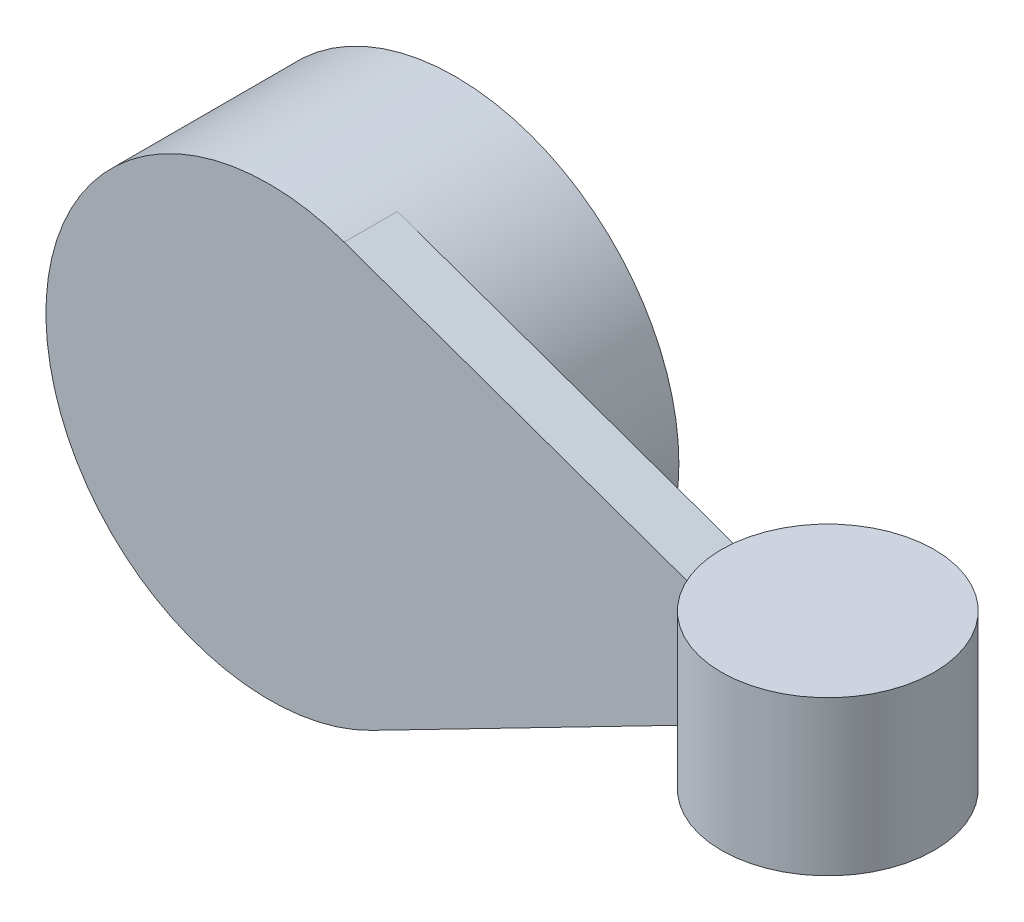
SolidWorks part; units mm, degrees
ref_plane "前视基准面" through (0, 0, 0) normal (0, 0, 1) x (1, 0, 0)
ref_plane "上视基准面" through (0, 0, 0) normal (0, 1, 0) x (1, 0, 0)
ref_plane "右视基准面" through (0, 0, 0) normal (1, 0, 0) x (0, 0, -1)
other "Configuration Table"
sketch "草图1" plane through (0, 0, 0) normal (0, 0, 1) x (1, 0, 0)
  circle A0 centre (0, 0) radius 42
  dimension "D1" = 84
extrude "凸台-拉伸1" add sketch "草图1" along normal blind 30
sketch "草图2" plane through (0, 0, 30) normal (0, 0, 1) x (1, 0, 0)
  line L0 (0, 0) -> (150.9371, 0) construction
  line L1 (100, 22.7173) -> (100, -21.6499) construction
  line L2 (100, 20) -> (100, 15)
  line L3 (80, 20) -> (100, 20)
  line L4 (80, 20) -> (80, -9)
  line L8 (80, -9) -> (88, -9)
  arc A1 (100, 15) -> (88, -9) centre (100, 0) ccw
  dimension "D2" = 30
  dimension "D1" = 100
  dimension "D3" = 20
  dimension "D4" = 20
  dimension "D5" = 9
revolve "旋转1" add sketch "草图2" angle 360 about L1
sketch "草图3" plane through (0, 0, 30) normal (0, 0, 1) x (1, 0, 0)
  line L0 (14.0695, 39.5734) -> (86, 14)
  line L1 (19.2087, -37.35) -> (86, -3)
  line L4 (86, 14) -> (86, -3)
  circle A1 centre (0, 0) radius 42
  arc A2 (14.0695, 39.5734) -> (19.2087, -37.35) centre (0, 0) ccw
  point P0 (86, -3.4559)
  dimension "D2" = 86
  dimension "D3" = 14
  dimension "D4" = 3
  dimension "D1" = 0
extrude "凸台-拉伸2" add sketch "草图3" along normal mid plane 10
